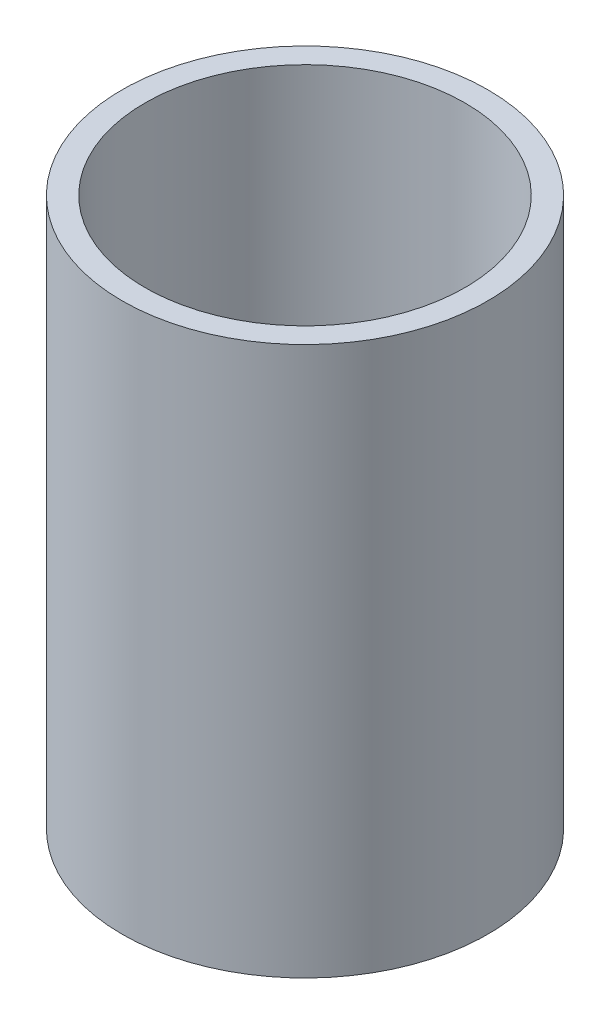
SolidWorks part; units mm, degrees
material "Copper"
ref_plane "Front Plane" through (0, 0, 0) normal (0, 0, 1) x (1, 0, 0)
ref_plane "Top Plane" through (0, 0, 0) normal (0, 1, 0) x (1, 0, 0)
ref_plane "Right Plane" through (0, 0, 0) normal (1, 0, 0) x (0, 0, -1)
sketch "Sketch1" plane through (0, 0, 0) normal (0, 1, 0) x (1, 0, 0)
  circle A0 centre (0, 0) radius 12.7
  circle A1 centre (0, 0) radius 11.1125
  dimension "D1" = 25.4
  dimension "D2" = 1.5875
extrude "Boss-Extrude1" add sketch "Sketch1" along normal blind 38.1
